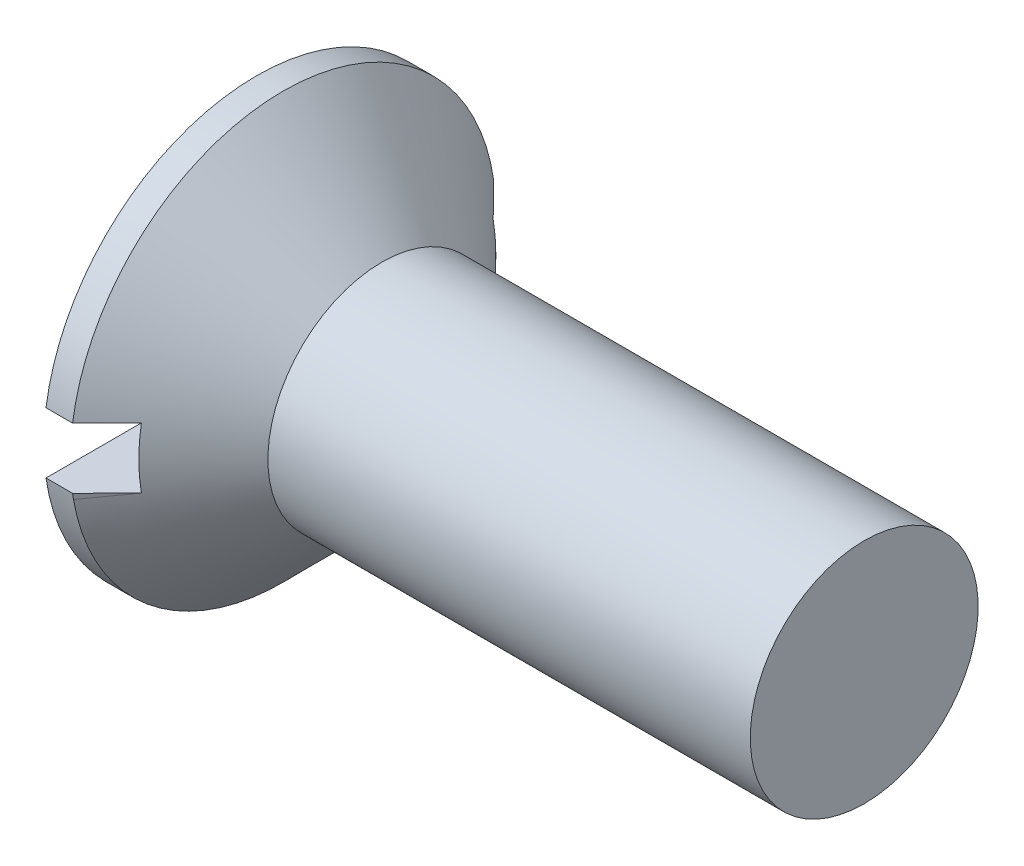
SolidWorks part; units mm, degrees
material "Plain Carbon Steel"
ref_plane "Front Plane" through (0, 0, 0) normal (0, 0, 1) x (1, 0, 0)
ref_plane "Top Plane" through (0, 0, 0) normal (0, 1, 0) x (1, 0, 0)
ref_plane "Right Plane" through (0, 0, 0) normal (1, 0, 0) x (0, 0, -1)
sketch "Sketch1" plane through (0, 0, 0) normal (0, 0, 1) x (1, 0, 0)
  line L0 (0, 0) -> (0, 2.8)
  line L1 (0, 2.8) -> (0.35, 2.8)
  line L2 (0.35, 2.8) -> (1.65, 1.5)
  line L3 (1.65, 1.5) -> (8, 1.5)
  line L4 (8, 1.5) -> (8, 0)
  line L5 (8, 0) -> (0, 0) construction
  line L6 (0, 0) -> (8, 0)
  dimension "D1" = 45
  dimension "D2" = 3
  dimension "D3" = 5.6
  dimension "D4" = 1.65
  dimension "D5" = 8
revolve "Revolve1" add sketch "Sketch1" angle 360 about L5
sketch "Sketch2" plane through (0, 0, 0) normal (-1, 0, 0) x (0, 0, 1)
  line L0 (2.8, 0) -> (-2.8, 0) construction
  line L1 (-2.8, 0.4) -> (2.8, 0.4)
  line L2 (-2.8, 0.4) -> (-2.8, -0.4)
  line L3 (-2.8, -0.4) -> (2.8, -0.4)
  line L4 (2.8, 0.4) -> (2.8, -0.4)
  circle A0 centre (0, 0) radius 2.8 construction
  dimension "D1" = 0.8
extrude "Cut-Extrude1" cut sketch "Sketch2" against normal blind 0.8
